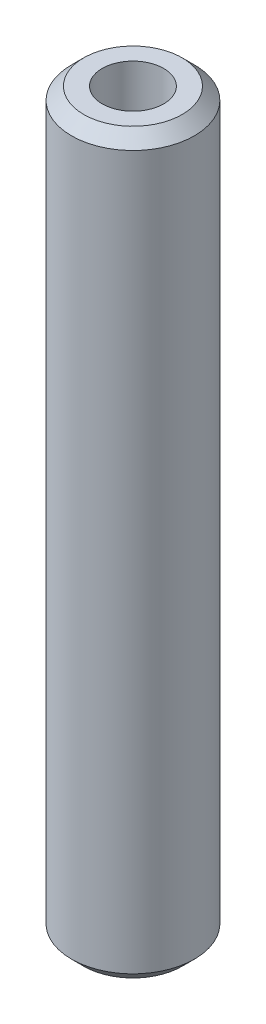
SolidWorks part; units mm, degrees
material "AISI 316 Stainless Steel Sheet (SS)"
ref_plane "Front Plane" through (0, 0, 0) normal (0, 0, 1) x (1, 0, 0)
ref_plane "Top Plane" through (0, 0, 0) normal (0, 1, 0) x (1, 0, 0)
ref_plane "Right Plane" through (0, 0, 0) normal (1, 0, 0) x (0, 0, -1)
sketch "Sketch1" plane through (0, 0, 0) normal (0, 1, 0) x (1, 0, 0)
  circle A0 centre (0, 0) radius 2.5
  dimension "D1" = 5
extrude "Boss-Extrude1" add sketch "Sketch1" along normal blind 30
cosmetic thread "Cosmetic Thread1" parameters "D1"=7, "D2"=4.11
hole_wizard "M3x0.5 Tapped Hole1" positions "Sketch2" profile "Sketch3" tap size "M3x0.5" standard "JIS"
sketch "Sketch2" plane through (0, 30, 0) normal (0, 1, 0) x (1, 0, 0)
  point P0 (0, 0)
sketch "Sketch3" plane through (0, 30, 0) normal (1, 0, 0) x (0, 0, 1)
  line L0 (0, 0) -> (0, 7.7511)
  line L1 (0, 7.7511) -> (1.25, 7)
  line L2 (1.25, 7) -> (1.25, 0)
  line L5 (1.25, 0) -> (0, 0)
  line L10 (0, 7.7511) -> (-1.25, 7) construction
  line L11 (0, -6.35) -> (0, 107.95) construction
  dimension "Tap Drill Dia." = 2.5
  dimension "Tap Drill Depth" = 7
  dimension "Drill Angle" = 118
cosmetic thread "Hole Thread1" parameters "D1"=5, "D2"=3
hole_wizard "M3x0.5 Tapped Hole2" positions "Sketch4" profile "Sketch5" tap size "M3x0.5" standard "JIS"
sketch "Sketch4" plane through (0, 0, 0) normal (0, -1, 0) x (-1, 0, 0)
  point P0 (0, 0)
sketch "Sketch5" plane through (0, 0, 0) normal (1, 0, 0) x (0, 0, -1)
  line L0 (0, 0) -> (0, 7.7511)
  line L1 (0, 7.7511) -> (1.25, 7)
  line L2 (1.25, 7) -> (1.25, 0)
  line L5 (1.25, 0) -> (0, 0)
  line L10 (0, 7.7511) -> (-1.25, 7) construction
  line L11 (0, -6.35) -> (0, 107.95) construction
  dimension "Tap Drill Dia." = 2.5
  dimension "Tap Drill Depth" = 7
  dimension "Drill Angle" = 118
cosmetic thread "Hole Thread2" parameters "D1"=5, "D2"=3
chamfer "Chamfer1" distance 0.5 angle 45 2 edges at (0, 0, 2.5) (0, 30, 2.5)
